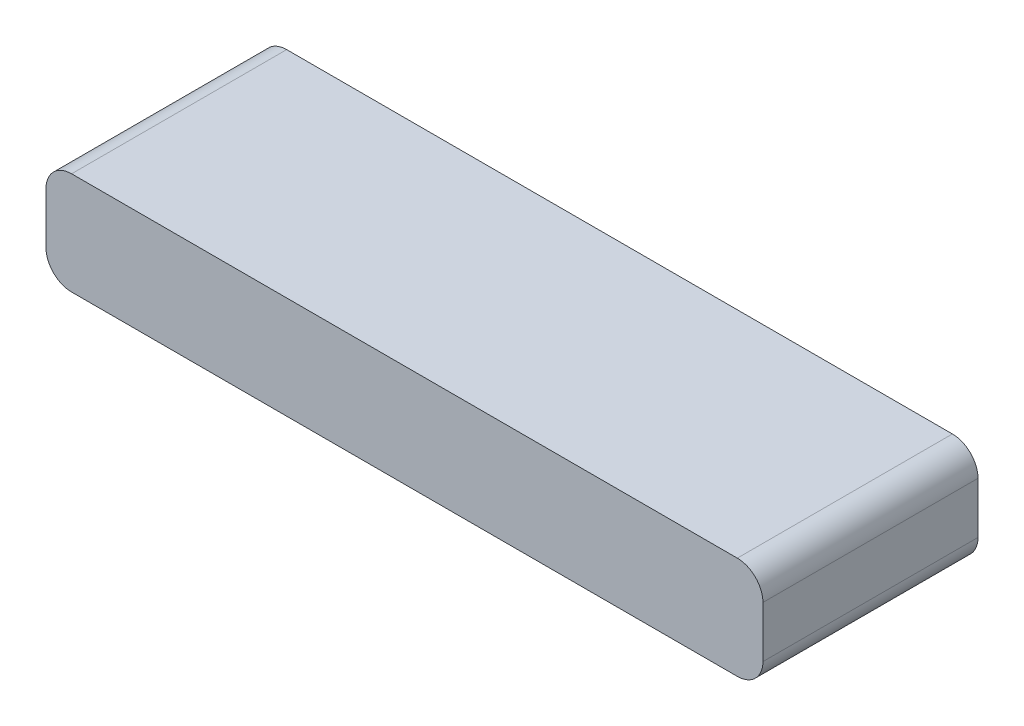
SolidWorks part; units mm, degrees
ref_plane "前视基准面" through (0, 0, 0) normal (0, 0, 1) x (1, 0, 0)
ref_plane "上视基准面" through (0, 0, 0) normal (0, 1, 0) x (1, 0, 0)
ref_plane "右视基准面" through (0, 0, 0) normal (1, 0, 0) x (0, 0, -1)
sketch "草图1" plane through (0, 0, 0) normal (0, 1, 0) x (1, 0, 0)
  line L0 (-106.7629, 0) -> (108.1801, 0) construction
  line L1 (0, 106.9991) -> (0, -103.6922) construction
  line L3 (-70, 21) -> (70, 21)
  line L4 (-70, 21) -> (-70, -21)
  line L5 (-70, -21) -> (70, -21)
  line L6 (70, 21) -> (70, -21)
  line L7 (-70, 21) -> (70, -21) construction
  line L8 (-70, -21) -> (70, 21) construction
  point P5 (0, 0)
  dimension "D1" = 140
  dimension "D2" = 42
extrude "凸台-拉伸1" add sketch "草图1" along normal blind 20
sketch "草图2" plane through (0, 0, 0) normal (0, -1, 0) x (1, 0, 0)
  line L0 (-77.66, 0) -> (79.2151, 0) construction
  line L1 (0, 0) -> (0, 5) construction
  line L3 (-10.5725, 12.4335) -> (10.5725, 12.4335)
  line L4 (-10.5725, 12.4335) -> (-10.5725, 5)
  line L5 (-10.5725, 5) -> (10.5725, 5)
  line L6 (10.5725, 12.4335) -> (10.5725, 5)
  line L7 (-10.5725, 12.4335) -> (10.5725, 5) construction
  line L8 (-10.5725, 5) -> (10.5725, 12.4335) construction
  point P5 (0, 8.7167)
  dimension "D1" = 5
extrude "凸台-拉伸2" add sketch "草图2" along normal blind 4
fillet "圆角1" radius 5 2 edges at (-70, 20, 0) (70, 20, 0)
fillet "圆角2" radius 5 2 edges at (-70, 0, 0) (70, 0, 0)
